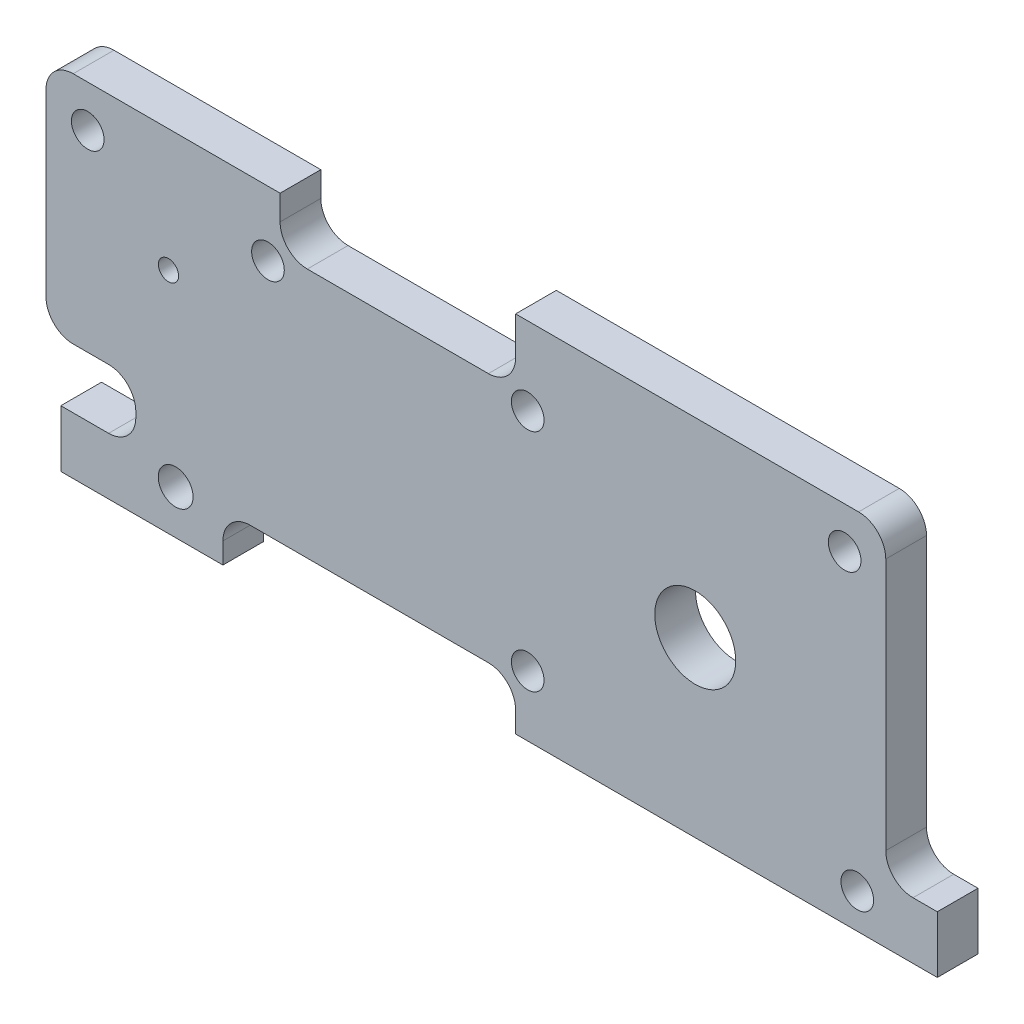
SolidWorks part; units mm, degrees
ref_plane "Front Plane" through (0, 0, 0) normal (0, 0, 1) x (1, 0, 0)
ref_plane "Top Plane" through (0, 0, 0) normal (0, 1, 0) x (1, 0, 0)
ref_plane "Right Plane" through (0, 0, 0) normal (1, 0, 0) x (0, 0, -1)
sketch "Sketch10" plane through (0, 0, 0) normal (0, 0, -1) x (-1, 0, 0)
  line L0 (-33.3871, 0.4566) -> (-54.6821, 21.7516) construction
  line L2 (-52.2874, 19.3569) -> (-52.2874, -15.6781) construction
  line L3 (11.8635, 18.2366) -> (-9.2571, 18.2366) construction
  line L4 (-9.2571, 18.2366) -> (1.3032, 23.5942) construction
  line L5 (1.3032, 23.5942) -> (1.3032, -17.7894) construction
  line L6 (2.4777, 0.4566) -> (-12.3051, 0.4566) construction
  line L7 (28.056, 6.8519) -> (41.4135, 20.2095) construction
  circle A0 centre (-33.3871, 0.4566) radius 4.7244
  circle A2 centre (-52.2874, -15.6781) radius 1.905
  circle A4 centre (28.056, 6.8519) radius 1.1793
  circle A5 centre (37.4743, 16.2702) radius 1.905
  circle A6 centre (-13.8463, 13.5969) radius 1.905
  circle A7 centre (-13.8463, -12.6838) radius 1.905
  circle A10 centre (27.2212, -14.6226) radius 2.032
  circle A11 centre (-50.815, 17.8845) radius 1.905
  circle A12 centre (16.4527, 13.5969) radius 1.905
sketch "Sketch4" plane through (0, 0, 0) normal (0, 0, 1) x (1, 0, 0)
  line L0 (-42.3435, -2.9906) -> (-42.3435, 17.9644)
  line L1 (-40.6186, -19.7615) -> (-21.7055, -19.7615)
  line L2 (12.4321, -17.3234) -> (12.4321, -19.7615)
  line L3 (-15.0385, 21.1394) -> (-39.1685, 21.1394)
  line L4 (55.6121, -9.9457) -> (55.6121, 19.5066)
  line L5 (61.6185, -19.7615) -> (61.6185, -13.1207)
  line L6 (61.6185, -13.1207) -> (58.7871, -13.1207)
  line L7 (-40.6186, -19.7615) -> (-40.6186, -13.1207)
  line L8 (-40.6186, -13.1207) -> (-35.0405, -13.1207)
  line L9 (-18.5305, -14.1484) -> (9.2571, -14.1484)
  line L10 (12.4321, 18.2366) -> (12.4321, 22.6816)
  line L11 (-21.7055, -17.3234) -> (-21.7055, -19.7615)
  line L12 (12.4321, -19.7615) -> (61.6185, -19.7615)
  line L13 (9.2571, 15.0616) -> (-11.8635, 15.0616)
  line L14 (-15.0385, 18.2366) -> (-15.0385, 21.1394)
  line L15 (52.4371, 22.6816) -> (12.4321, 22.6816)
  line L16 (-39.1685, -6.1656) -> (-35.0405, -6.1656)
  line L17 (-31.8655, -9.3406) -> (-31.8655, -9.9457)
  arc A0 (-39.1685, 21.1394) -> (-42.3435, 17.9644) centre (-39.1685, 17.9644) ccw
  arc A1 (-42.3435, -2.9906) -> (-39.1685, -6.1656) centre (-39.1685, -2.9906) ccw
  arc A2 (-31.8655, -9.3406) -> (-35.0405, -6.1656) centre (-35.0405, -9.3406) ccw
  arc A3 (-31.8655, -9.9457) -> (-35.0405, -13.1207) centre (-35.0405, -9.9457) cw
  arc A4 (-18.5305, -14.1484) -> (-21.7055, -17.3234) centre (-18.5305, -17.3234) ccw
  arc A5 (12.4321, -17.3234) -> (9.2571, -14.1484) centre (9.2571, -17.3234) ccw
  arc A6 (55.6121, -9.9457) -> (58.7871, -13.1207) centre (58.7871, -9.9457) ccw
  arc A7 (55.6121, 19.5066) -> (52.4371, 22.6816) centre (52.4371, 19.5066) ccw
  arc A8 (12.4321, 18.2366) -> (9.2571, 15.0616) centre (9.2571, 18.2366) cw
  arc A9 (-11.8635, 15.0616) -> (-15.0385, 18.2366) centre (-11.8635, 18.2366) cw
  circle A12 centre (-27.2212, -14.6226) radius 2.032
  circle A14 centre (-28.056, 6.8519) radius 1.1793
  circle A16 centre (52.2874, -15.6781) radius 1.905
  circle A18 centre (33.3871, 0.4566) radius 4.7244
  circle A20 centre (13.8463, -12.6838) radius 1.905
  circle A22 centre (13.8463, 13.5969) radius 1.905
  circle A24 centre (-37.4743, 16.2702) radius 1.905
  circle A26 centre (-16.4527, 13.5969) radius 1.905
  circle A28 centre (50.815, 17.8845) radius 1.905
extrude "Extrude3" add sketch "Sketch4" along normal blind 4.7498 separate body
